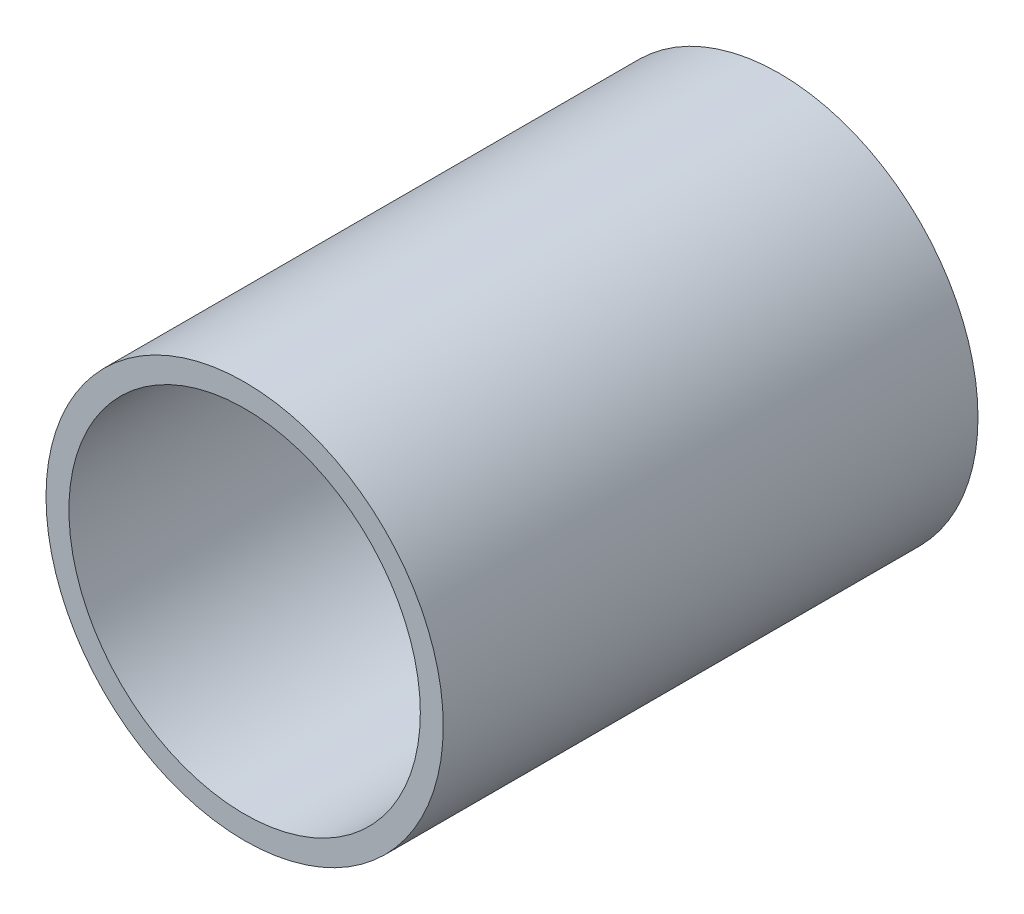
SolidWorks part; units mm, degrees
ref_plane "Front Plane" through (0, 0, 0) normal (0, 0, 1) x (1, 0, 0)
ref_plane "Top Plane" through (0, 0, 0) normal (0, 1, 0) x (1, 0, 0)
ref_plane "Right Plane" through (0, 0, 0) normal (1, 0, 0) x (0, 0, -1)
sketch "Sketch1" plane through (0, 0, 0) normal (0, 0, 1) x (1, 0, 0)
  circle A0 centre (0, 0) radius 23
  circle A1 centre (0, 0) radius 26
  dimension "D1" = 46
  dimension "D2" = 52
extrude "Boss-Extrude1" add sketch "Sketch1" along normal mid plane 70
